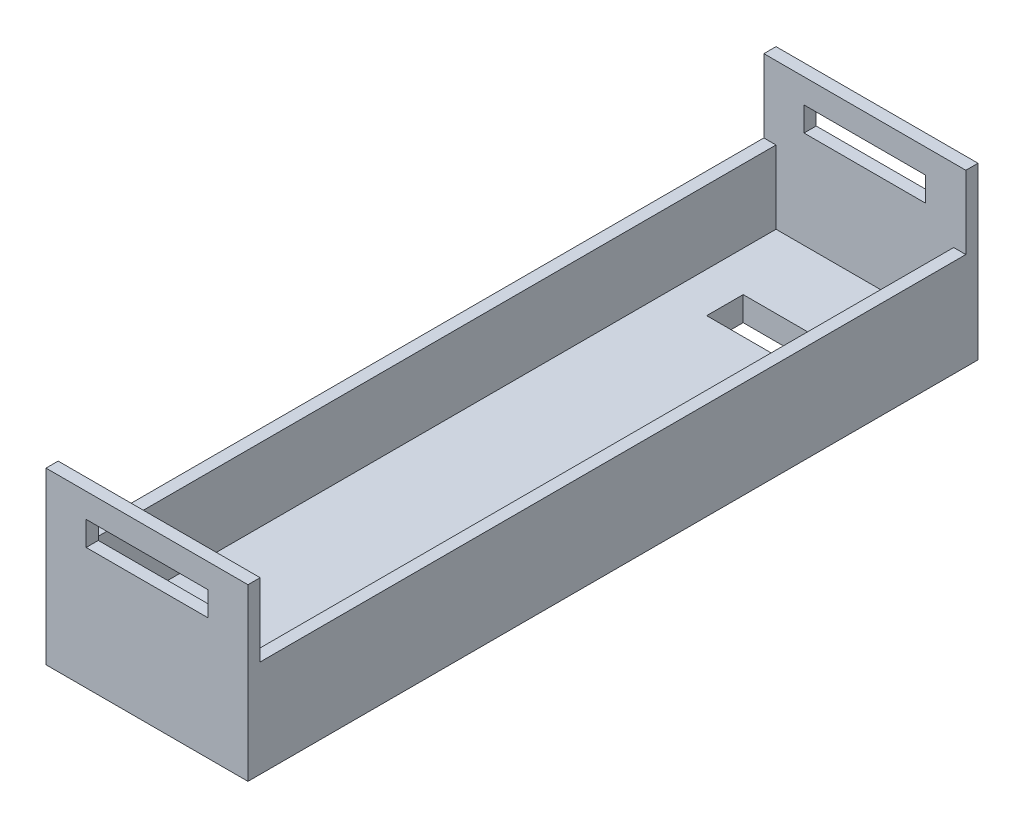
SolidWorks part; units mm, degrees
ref_plane "Front Plane" through (0, 0, 0) normal (0, 0, 1) x (1, 0, 0)
ref_plane "Top Plane" through (0, 0, 0) normal (0, 1, 0) x (1, 0, 0)
ref_plane "Right Plane" through (0, 0, 0) normal (1, 0, 0) x (0, 0, -1)
sketch "Sketch1" plane through (0, 0, 0) normal (0, 0, 1) x (1, 0, 0)
  line L1 (41.5, -35) -> (-41.5, -35)
  line L2 (41.5, -35) -> (41.5, 35)
  line L3 (41.5, 35) -> (-41.5, 35)
  line L4 (-41.5, -35) -> (-41.5, 35)
  line L5 (41.5, -35) -> (-41.5, 35) construction
  line L6 (41.5, 35) -> (-41.5, -35) construction
  point P0 (0, 0)
  dimension "D1" = 70
  dimension "D2" = 83
extrude "Boss-Extrude1" add sketch "Sketch1" along normal mid plane 300
sketch "Sketch2" plane through (0, 35, 0) normal (0, 1, 0) x (1, 0, 0)
  line L0 (36.5, 145) -> (-36.5, 145)
  line L1 (-36.5, 145) -> (-36.5, -145)
  line L2 (-36.5, -145) -> (36.5, -145)
  line L3 (36.5, -145) -> (36.5, 145)
  line L4 (41.5, 150) -> (-41.5, 150)
  line L5 (-41.5, 150) -> (-41.5, -150)
  line L6 (-41.5, -150) -> (41.5, -150)
  line L7 (41.5, -150) -> (41.5, 150)
  line L8 (41.5, 150) -> (-41.5, 150) construction
  line L9 (-41.5, 150) -> (-41.5, -150) construction
  line L10 (-41.5, -150) -> (41.5, -150) construction
  line L11 (41.5, -150) -> (41.5, 150) construction
  dimension "D1" = 0
  dimension "D2" = 5
extrude "Cut-Extrude1" cut sketch "Sketch2" against normal blind 60
sketch "Sketch3" plane through (-41.5, 0, 0) normal (-1, 0, 0) x (0, 0, 1)
  line L0 (150, 35) -> (-150, 35) construction
  line L1 (-145, 35) -> (145, 35)
  line L2 (-145, 35) -> (-145, 5)
  line L3 (-145, 5) -> (145, 5)
  line L4 (145, 35) -> (145, 5)
  line L5 (-150, 35) -> (-150, -35) construction
  line L6 (150, 35) -> (150, -35) construction
  dimension "D1" = 5
  dimension "D2" = 5
  dimension "D3" = 30
extrude "Cut-Extrude2" cut sketch "Sketch3" against normal blind 109
sketch "Sketch4" plane through (0, 0, 150) normal (0, 0, 1) x (1, 0, 0)
  line L1 (-25, 15) -> (25, 15)
  line L2 (-25, 15) -> (-25, 25)
  line L3 (-25, 25) -> (25, 25)
  line L4 (25, 15) -> (25, 25)
  point P4 (0, 15)
  dimension "D1" = 50
  dimension "D2" = 10
  dimension "D3" = 15
extrude "Cut-Extrude3" cut sketch "Sketch4" against normal blind 343
sketch "Sketch5" plane through (0, -25, 0) normal (0, 1, 0) x (1, 0, 0)
  line L1 (-20, 115) -> (20, 115)
  line L2 (-20, 115) -> (-20, 100)
  line L3 (-20, 100) -> (20, 100)
  line L4 (20, 115) -> (20, 100)
  line L5 (-20, 115) -> (20, 100) construction
  line L6 (-20, 100) -> (20, 115) construction
  point P0 (0, 107.5)
  point P5 (0, 102.3985)
  point P6 (0, 0)
  dimension "D1" = 40
  dimension "D2" = 15
  dimension "D3" = 100
extrude "Cut-Extrude4" cut sketch "Sketch5" against normal blind 343
